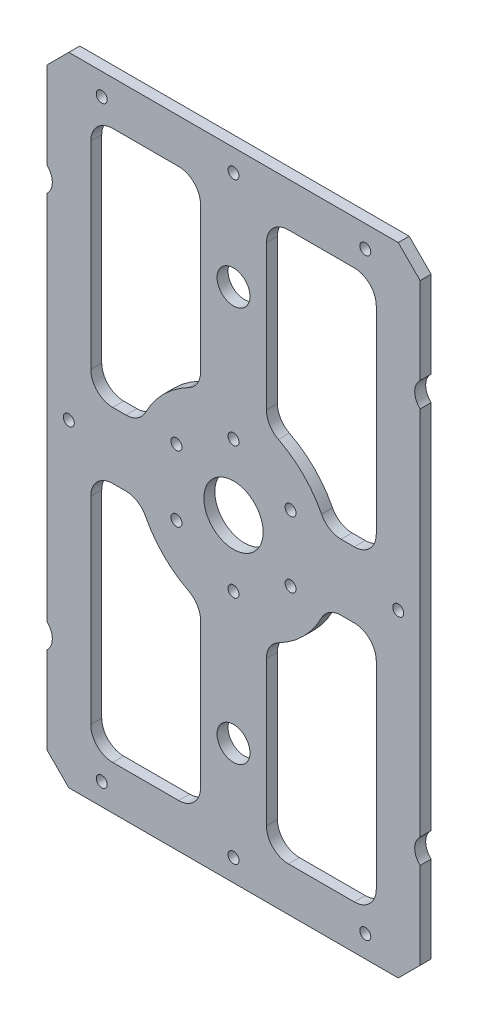
SolidWorks part; units mm, degrees
ref_plane "正面" through (0, 0, 0) normal (0, 0, 1) x (1, 0, 0)
ref_plane "平面" through (0, 0, 0) normal (0, 1, 0) x (1, 0, 0)
ref_plane "右側面" through (0, 0, 0) normal (1, 0, 0) x (0, 0, -1)
sketch "ｽｹｯﾁ1" plane through (0, 0, 0) normal (0, 0, 1) x (1, 0, 0)
  line L1 (-85, 145) -> (85, 145)
  line L2 (-85, 145) -> (-85, -145)
  line L3 (-85, -145) -> (85, -145)
  line L4 (85, 145) -> (85, -145)
  line L5 (-85, 145) -> (85, -145) construction
  line L6 (-85, -145) -> (85, 145) construction
  point P0 (0, 0)
  dimension "D1" = 170
  dimension "D2" = 290
extrude "ﾎﾞｽ - 押し出し1" add sketch "ｽｹｯﾁ1" along normal blind 5
sketch "ｽｹｯﾁ2" plane through (0, 0, 5) normal (0, 0, 1) x (1, 0, 0)
  circle A0 centre (0, 0) radius 13.5
  dimension "D1" = 27
extrude "ｶｯﾄ - 押し出し1" cut sketch "ｽｹｯﾁ2" against normal through all
sketch "ｽｹｯﾁ3" plane through (0, 0, 5) normal (0, 0, 1) x (1, 0, 0)
  line L0 (85, -145) -> (85, 145) construction
  line L1 (-75, 135) -> (75, 135) construction
  line L2 (-75, 135) -> (-75, -135) construction
  line L3 (-75, -135) -> (75, -135) construction
  line L4 (75, 135) -> (75, -135) construction
  line L5 (-75, 135) -> (75, -135) construction
  line L6 (-75, -135) -> (75, 135) construction
  line L7 (85, 145) -> (-85, 145) construction
  line L8 (-85, 0) -> (85, 0) construction
  line L9 (-85, 145) -> (-85, -145) construction
  line L10 (0, 145) -> (0, -145) construction
  line L11 (-85, -145) -> (85, -145) construction
  line L12 (-60, 135) -> (-60, -135) construction
  line L13 (60, 135) -> (60, -135) construction
  circle A0 centre (-75, 0) radius 2.5
  circle A1 centre (0, 135) radius 2.5
  circle A2 centre (75, 0) radius 2.5
  circle A3 centre (0, -135) radius 2.5
  circle A4 centre (-60, 135) radius 2.5
  circle A5 centre (60, 135) radius 2.5
  circle A6 centre (60, -135) radius 2.5
  circle A7 centre (-60, -135) radius 2.5
  point P0 (0, 0)
  dimension "D3" = 5
  dimension "D1" = 10
  dimension "D2" = 10
  dimension "D4" = 60
extrude "ｶｯﾄ - 押し出し2" cut sketch "ｽｹｯﾁ3" against normal through all
chamfer "面取り1" distance 10 angle 45 4 edges at (85, -145, 2.5) (-85, -145, 2.5) (-85, 145, 2.5) (85, 145, 2.5)
sketch "ｽｹｯﾁ4" plane through (0, 0, 5) normal (0, 0, 1) x (1, 0, 0)
  line L0 (0, 0) -> (0, 90) construction
  line L1 (0, 90) -> (90, 90) construction
  line L2 (-75, 0) -> (75, 0) construction
  line L3 (0, 0) -> (0, -30) construction
  line L4 (0, 0) -> (-25.9808, 15) construction
  line L5 (0, 0) -> (25.9808, 15) construction
  circle A0 centre (90, 90) radius 7.5
  circle A1 centre (0, 90) radius 7.5
  circle A2 centre (-90, 90) radius 7.5
  circle A4 centre (-90, -90) radius 7.5
  circle A5 centre (0, -90) radius 7.5
  circle A6 centre (90, -90) radius 7.5
  circle A8 centre (0, -30) radius 2.5
  circle A9 centre (-25.9808, -15) radius 2.5
  circle A10 centre (-25.9808, 15) radius 2.5
  circle A11 centre (0, 30) radius 2.5
  circle A12 centre (25.9808, 15) radius 2.5
  circle A13 centre (25.9808, -15) radius 2.5
  dimension "D1" = 90
  dimension "D3" = 15
  dimension "D4" = 6
  dimension "D6" = 5
  dimension "D2" = 90
  dimension "D5" = 30
extrude "ｶｯﾄ - 押し出し3" cut sketch "ｽｹｯﾁ4" against normal through all
sketch "ｽｹｯﾁ5" plane through (0, 0, 5) normal (0, 0, 1) x (1, 0, 0)
  line L0 (-65, 125) -> (-65, 15)
  line L1 (-65, 15) -> (-42.4264, 15)
  line L4 (-15, 42.4264) -> (-15, 125)
  line L5 (-15, 125) -> (-65, 125)
  line L6 (-85, 84.4098) -> (-85, -84.4098) construction
  line L7 (75, 145) -> (-75, 145) construction
  line L8 (0, 145) -> (0, 0) construction
  line L9 (0, 0) -> (-85, 0) construction
  line L10 (15, 42.4264) -> (15, 125)
  line L11 (15, 125) -> (65, 125)
  line L12 (65, 125) -> (65, 15)
  line L13 (65, 15) -> (42.4264, 15)
  line L14 (-15, -42.4264) -> (-15, -125)
  line L15 (-15, -125) -> (-65, -125)
  line L16 (-65, -125) -> (-65, -15)
  line L17 (-65, -15) -> (-42.4264, -15)
  line L18 (15, -42.4264) -> (15, -125)
  line L19 (15, -125) -> (65, -125)
  line L20 (65, -125) -> (65, -15)
  line L21 (65, -15) -> (42.4264, -15)
  arc A0 (-15, 42.4264) -> (-42.4264, 15) centre (0, 0) ccw
  arc A1 (15, 42.4264) -> (42.4264, 15) centre (0, 0) cw
  arc A2 (-15, -42.4264) -> (-42.4264, -15) centre (0, 0) cw
  arc A3 (15, -42.4264) -> (42.4264, -15) centre (0, 0) ccw
  dimension "D1" = 45
  dimension "D2" = 20
  dimension "D3" = 20
  dimension "D4" = 15
  dimension "D5" = 15
extrude "ｶｯﾄ - 押し出し4" cut sketch "ｽｹｯﾁ5" against normal through all
fillet "ﾌｨﾚｯﾄ1" radius 10 20 edges at (-65, -15, 2.5) (-15, -125, 2.5) (-65, -125, 2.5) (-15, -42.4264, 2.5) (-42.4264, -15, 2.5) (15, -125, 2.5) (15, -42.4264, 2.5) (42.4264, -15, 2.5) (65, -15, 2.5) (65, -125, 2.5) (65, 15, 2.5) (65, 125, 2.5) (15, 125, 2.5) (42.4264, 15, 2.5) (15, 42.4264, 2.5) (-15, 42.4264, 2.5) (-42.4264, 15, 2.5) (-65, 15, 2.5) (-15, 125, 2.5) (-65, 125, 2.5)
